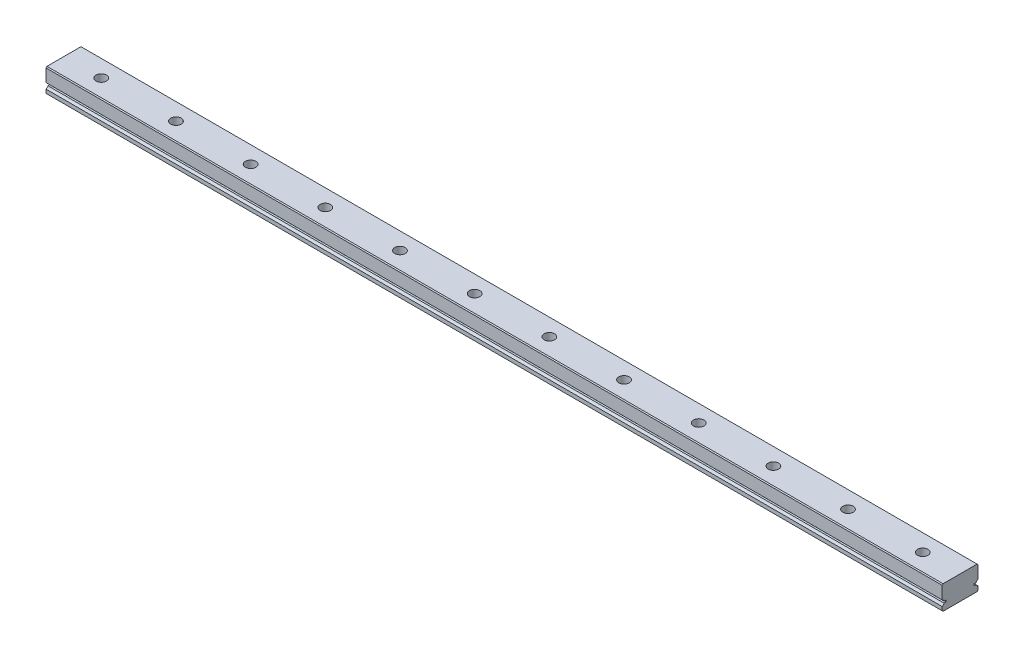
SolidWorks part; units mm, degrees
ref_plane "Front Plane" through (0, 0, 0) normal (0, 0, 1) x (1, 0, 0)
ref_plane "Top Plane" through (0, 0, 0) normal (0, 1, 0) x (1, 0, 0)
ref_plane "Right Plane" through (0, 0, 0) normal (1, 0, 0) x (0, 0, -1)
ref_plane "Plane1" through (0, -100.8498, 0) normal (0, -1, 0) x (1, 0, 0)
sketch "Sketch1" plane through (0, -100.8498, 0) normal (0, -1, 0) x (1, 0, 0)
  line L0 (-319.6712, 667.1515) -> (-319.6712, 655.1515)
  line L1 (-319.6712, 655.1515) -> (80.3288, 655.1515)
  line L2 (80.3288, 655.1515) -> (80.3288, 667.1515)
  line L3 (80.3288, 667.1515) -> (-319.6712, 667.1515)
  dimension "D1" = 400
extrude "Boss-Extrude1" add sketch "Sketch1" against normal blind 8
sketch "Sketch2" plane through (80.3288, 0, 0) normal (1, 0, 0) x (0, 0, -1)
  line L0 (-655.1515, -98.6479) -> (-655.1515, -97.3988)
  line L1 (-655.7969, -98.0518) -> (-656.508, -98.0518)
  line L2 (-656.508, -98.0518) -> (-656.508, -98.6479)
  line L3 (-656.508, -98.6479) -> (-655.1515, -98.6479)
  arc A0 (-655.1515, -97.3988) -> (-655.7969, -98.0518) centre (-654.8424, -98.3498) ccw
extrude "Cut-Extrude1" cut sketch "Sketch2" against normal through all
sketch "Sketch3" plane through (80.3288, 0, 0) normal (1, 0, 0) x (0, 0, -1)
  line L0 (-655.1515, -99.3009) -> (-655.1515, -98.6479)
  line L1 (-655.1515, -98.6479) -> (-655.7969, -98.6479)
  arc A0 (-655.7969, -98.6479) -> (-655.1515, -99.3009) centre (-654.8424, -98.3498) ccw
extrude "Cut-Extrude2" cut sketch "Sketch3" against normal through all
sketch "Sketch4" plane through (80.3288, 0, 0) normal (1, 0, 0) x (0, 0, -1)
  line L0 (-667.1515, -98.0518) -> (-667.1515, -99.3009)
  line L1 (-666.5061, -98.6479) -> (-665.7951, -98.6479)
  line L2 (-665.7951, -98.6479) -> (-665.7951, -98.0518)
  line L3 (-665.7951, -98.0518) -> (-667.1515, -98.0518)
  arc A0 (-667.1515, -99.3009) -> (-666.5061, -98.6479) centre (-667.4607, -98.3498) ccw
extrude "Cut-Extrude3" cut sketch "Sketch4" against normal through all
sketch "Sketch5" plane through (80.3288, 0, 0) normal (1, 0, 0) x (0, 0, -1)
  line L0 (-667.1515, -97.3988) -> (-667.1515, -98.0518)
  line L1 (-667.1515, -98.0518) -> (-666.5061, -98.0518)
  arc A0 (-666.5061, -98.0518) -> (-667.1515, -97.3988) centre (-667.4607, -98.3498) ccw
extrude "Cut-Extrude4" cut sketch "Sketch5" against normal through all
hole_wizard "CBORE for M3 Hex Head Machine Screw1" positions "Sketch7" profile "Sketch6" counterbore size "M3" standard "ANSI Metric"
sketch "Sketch7" plane through (0, -100.8498, 0) normal (0, -1, 0) x (-1, 0, 0)
  point P0 (282.1712, -661.1515)
  point P1 (307.1712, -661.1515)
  point P2 (257.1712, -661.1515)
  point P3 (232.1712, -661.1515)
  point P4 (207.1712, -661.1515)
  point P5 (182.1712, -661.1515)
  point P6 (132.1712, -661.1515)
  point P7 (157.1712, -661.1515)
  point P8 (107.1712, -661.1515)
  point P9 (82.1712, -661.1515)
  point P10 (-67.8288, -661.1515)
  point P11 (-42.8288, -661.1515)
  point P12 (-17.8288, -661.1515)
  point P13 (7.1712, -661.1515)
  point P14 (32.1712, -661.1515)
  point P15 (57.1712, -661.1515)
sketch "Sketch6" plane through (-282.1712, -100.8498, 661.1515) normal (1, 0, 0) x (0, 0, -1)
  line L0 (0, 0) -> (0, 8)
  line L1 (0, 8) -> (1.75, 8)
  line L3 (1.75, 8) -> (1.75, 4.5)
  line L4 (1.75, 4.5) -> (3, 4.5)
  line L5 (3, 4.5) -> (3, 0)
  line L7 (3, 0) -> (0, 0)
  line L11 (0, -6.35) -> (0, 107.95) construction
  dimension "Thru Hole Dia." = 3.5
  dimension "Thru Hole Depth" = 8
  dimension "C'Bore Dia." = 6
  dimension "C'Bore Depth" = 4.5
chamfer "Chamfer1" distance 0.3 angle 45 4 edges at (-119.6712, -92.8498, 655.1515) (-119.6712, -92.8498, 667.1515) (-119.6712, -100.8498, 655.1515) (-119.6712, -100.8498, 667.1515)
sketch "Sketch8" plane through (0, -92.8498, 0) normal (0, 1, 0) x (1, 0, 0)
  line L1 (-19.6712, -667.1515) -> (199.4281, -667.1515)
  line L2 (-19.6712, -667.1515) -> (-19.6712, -614.4076)
  line L3 (-19.6712, -614.4076) -> (199.4281, -614.4076)
  line L4 (199.4281, -667.1515) -> (199.4281, -614.4076)
  line L6 (80.3288, -655.4515) -> (80.3288, -666.8515) construction
  line L8 (80.3288, -667.1515) -> (-319.6712, -667.1515) construction
  dimension "D1" = 100
extrude "Cut-Extrude5" cut sketch "Sketch8" against normal through all
